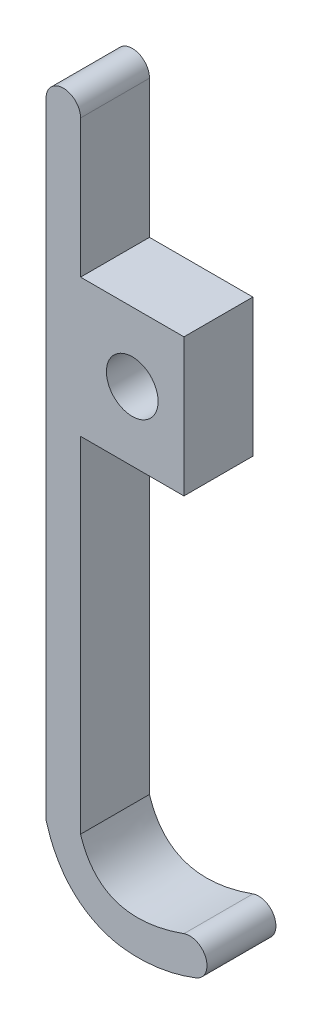
SolidWorks part; units mm, degrees
ref_plane "Alzado" through (0, 0, 0) normal (0, 0, 1) x (1, 0, 0)
ref_plane "Planta" through (0, 0, 0) normal (0, 1, 0) x (1, 0, 0)
ref_plane "Vista lateral" through (0, 0, 0) normal (1, 0, 0) x (0, 0, -1)
sketch "Croquis1" plane through (0, 0, 0) normal (0, 0, 1) x (1, 0, 0)
  line L0 (0, 0) -> (0, -18)
  line L1 (-1, 0) -> (-1, -18.1551)
  arc A0 (0, 0) -> (-1, 0) centre (-0.5, 0) ccw
  arc A1 (3, -19) -> (3.3369, -19.9416) centre (3.1684, -19.4708) cw
  spline S0 degree 2 poles (0, -18) (0.5915, -19.8617) (3, -19) knots 0 0 0 1 1 1
  spline S1 degree 1 poles (-1, -18.1551) (3.3369, -19.9416) knots 0 0 1 1 construction
  spline S2 degree 2 poles (-1, -18.1551) (-0.9759, -18.2327) (-0.8994, -18.4664) (-0.7561, -18.8178) (-0.4549, -19.3179) (0.028, -19.7929) (0.7773, -20.1973) (2.2762, -20.3524) (3.3369, -19.9416) knots -0.039688 -0.039688 -0.039688 0.009047 0.057783 0.155253 0.285214 0.415175 0.610117 1 1 1
  dimension "D2" = 3
  dimension "D4" = 0.75
  dimension "D1" = 18
  dimension "D3" = 1
  dimension "D5" = 0.4
  dimension "D6" = 1
extrude "Saliente-Extruir1" add sketch "Croquis1" along normal blind 2
sketch "Croquis2" plane through (0, 0, 0) normal (1, 0, 0) x (0, 0, -1)
  line L0 (0, 0) -> (0, 0.5) construction
  line L1 (-2, 0.5) -> (-2, 0) construction
  line L2 (0, 0.5) -> (-2, 0.5) construction
  line L3 (0, 0) -> (0, 0.5)
  line L4 (0, -18) -> (0, 0)
  line L5 (0, 0) -> (-2, 0)
  line L6 (-2, 0) -> (-2, -18)
  line L7 (-2, -18) -> (0, -18)
  line L8 (0, -18) -> (0, 0)
  line L9 (0, 0) -> (-2, 0)
  line L10 (-2, 0) -> (-2, -18)
  line L11 (-2, -18) -> (0, -18)
  line L12 (-2, 0.5) -> (-2, 0)
  line L13 (0, 0.5) -> (-2, 0.5)
  line L15 (-2, 0.5) -> (0, 0.5)
  line L16 (-2, 0.5) -> (-2, -1)
  line L17 (-2, -1) -> (0, -1)
  line L18 (0, 0.5) -> (0, -1)
  dimension "D2" = 1.5
  dimension "D1" = 0
sketch "Croquis3" plane through (0, 0, 0) normal (0, 0, -1) x (-1, 0, 0)
  line L0 (0, -18) -> (0, -4) construction
  line L1 (0, 0) -> (0, -18) construction
  line L2 (-3, -4) -> (0, -8) construction
  line L3 (0, -4) -> (-3, -4)
  line L4 (0, -4) -> (0, -8)
  line L5 (0, -8) -> (-3, -8)
  line L6 (-3, -4) -> (-3, -8)
  circle A0 centre (-1.5, -6) radius 0.75
  dimension "D4" = 1.5
  dimension "D1" = 14
  dimension "D2" = 3
  dimension "D3" = 4
extrude "Saliente-Extruir2" add sketch "Croquis3" against normal up to surface (2 mm away) up to face at (0.6899, -12.3392, 2)
